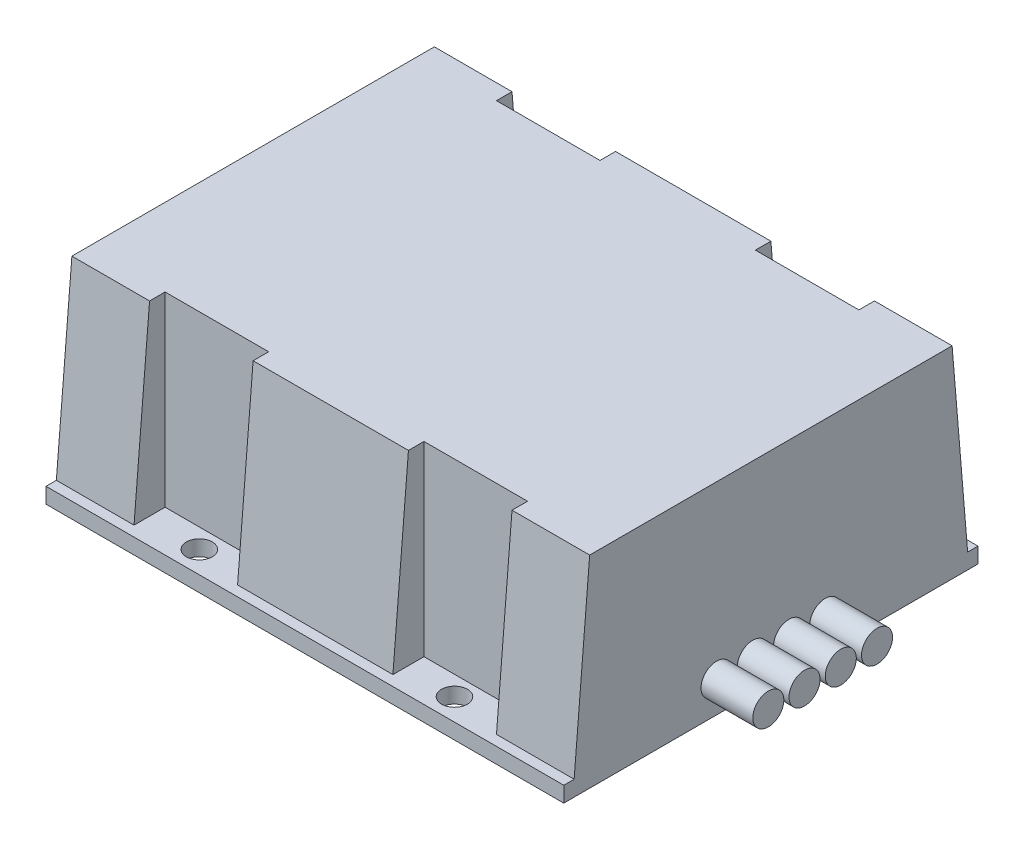
SolidWorks part; units mm, degrees
ref_plane "前视基准面" through (0, 0, 0) normal (0, 0, 1) x (1, 0, 0)
ref_plane "上视基准面" through (0, 0, 0) normal (0, 1, 0) x (1, 0, 0)
ref_plane "右视基准面" through (0, 0, 0) normal (1, 0, 0) x (0, 0, -1)
sketch "草图1" plane through (0, 0, 0) normal (0, 1, 0) x (1, 0, 0)
  line L1 (0, 0) -> (100, 0)
  line L2 (0, 0) -> (0, -80)
  line L3 (0, -80) -> (100, -80)
  line L4 (100, 0) -> (100, -80)
extrude "凸台-拉伸1" add sketch "草图1" along normal blind 39
sketch "草图5" plane through (100, 0, 0) normal (1, 0, 0) x (0, 0, -1)
  circle A0 centre (-50.5, 6) radius 3
  circle A1 centre (-43.5, 6) radius 3
  circle A2 centre (-36.5, 6) radius 3
  circle A3 centre (-29.5, 6) radius 3
  dimension "D1" = 4
extrude "凸台-拉伸3" add sketch "草图5" along normal blind 10
sketch "草图8" plane through (100, 0, 0) normal (1, 0, 0) x (0, 0, -1)
  line L0 (0, 39) -> (-5, 39)
  line L1 (-80, 39) -> (-80, 0) construction
  line L2 (-80, 3) -> (-78, 3)
  line L3 (-80, 39) -> (0, 39) construction
  line L4 (-75, 39) -> (-80, 39)
  line L5 (-80, 39) -> (-80, 3)
  line L6 (-75, 39) -> (-78, 3)
  line L7 (-40, 0) -> (-40, 39)
  line L8 (-80, 0) -> (0, 0) construction
  line L9 (0, 3) -> (-2, 3)
  line L10 (0, 39) -> (0, 3)
  line L11 (-5, 39) -> (-2, 3)
  line L12 (-5, 39) -> (0, 39)
  line M4 (0, 0) -> (0, 39)
  line M5 (0, 39) -> (-80, 39)
  line M6 (-80, 39) -> (-80, 0)
extrude "切除-拉伸1" cut sketch "草图8" against normal blind 1000 contours L6 L2 M5 M6 | L11 L9 M5 M4
sketch "草图9" plane through (0, 39, 0) normal (0, 1, 0) x (1, 0, 0)
  line L1 (0, -5) -> (100, -5) construction
  line L2 (35, -8) -> (15, -8)
  line L3 (35, -8) -> (35, 1.4795)
  line L5 (15, -5) -> (15, -8)
  line L6 (15, -8) -> (35, -8)
  line L7 (35, -5) -> (35, -8)
  line L9 (35, 1.4795) -> (15, 1.4795)
  line L12 (35, -75) -> (35, -72)
  line L13 (15, -72) -> (35, -72)
  line L14 (15, -75) -> (15, -72)
  line L16 (15, -75) -> (35, -75)
  line L19 (85, -75) -> (85, -72)
  line L20 (85, -72) -> (65, -72)
  line L21 (65, -75) -> (65, -72)
  line L22 (65, -5) -> (65, -8)
  line L23 (85, -8) -> (65, -8)
  line L24 (85, -5) -> (85, -8)
  line L25 (15, -72) -> (35, -72)
  line L27 (15, -8) -> (15, 1.4795)
  line L28 (65, -8) -> (85, -8)
  line L29 (65, -8) -> (65, 3.5197)
  line L30 (65, 3.5197) -> (85, 3.5197)
  line L31 (85, -8) -> (85, 3.5197)
  line L32 (15, -72) -> (15, -83.801)
  line L33 (15, -83.801) -> (35, -83.801)
  line L34 (35, -72) -> (35, -83.801)
  line L35 (65, -72) -> (85, -72)
  line L36 (65, -72) -> (65, -86.1022)
  line L37 (65, -86.1022) -> (85, -86.1022)
  line L38 (85, -72) -> (85, -86.1022)
  line M1 (100, -5) -> (0, -5)
  line M3 (0, -75) -> (100, -75)
extrude "切除-拉伸3" cut sketch "草图9" against normal blind 36 contours L27 L3 L9 M1 | L5 L2 L3 M1 | L31 L30 L29 M1 | L24 L22 L23 M1 | L38 L36 L37 M3 | L21 L19 L20 M3 | L34 L32 L33 M3 | L14 L12 L13 M3
sketch "草图10" plane through (0, 3, 0) normal (0, 1, 0) x (1, 0, 0)
  circle A0 centre (25, -4) radius 2.5
  circle A1 centre (25.3587, -75.7482) radius 2.5
  circle A2 centre (75, -4) radius 2.5
  circle A3 centre (74.6413, -75.7482) radius 2.5
extrude "切除-拉伸4" cut sketch "草图10" against normal blind 36
